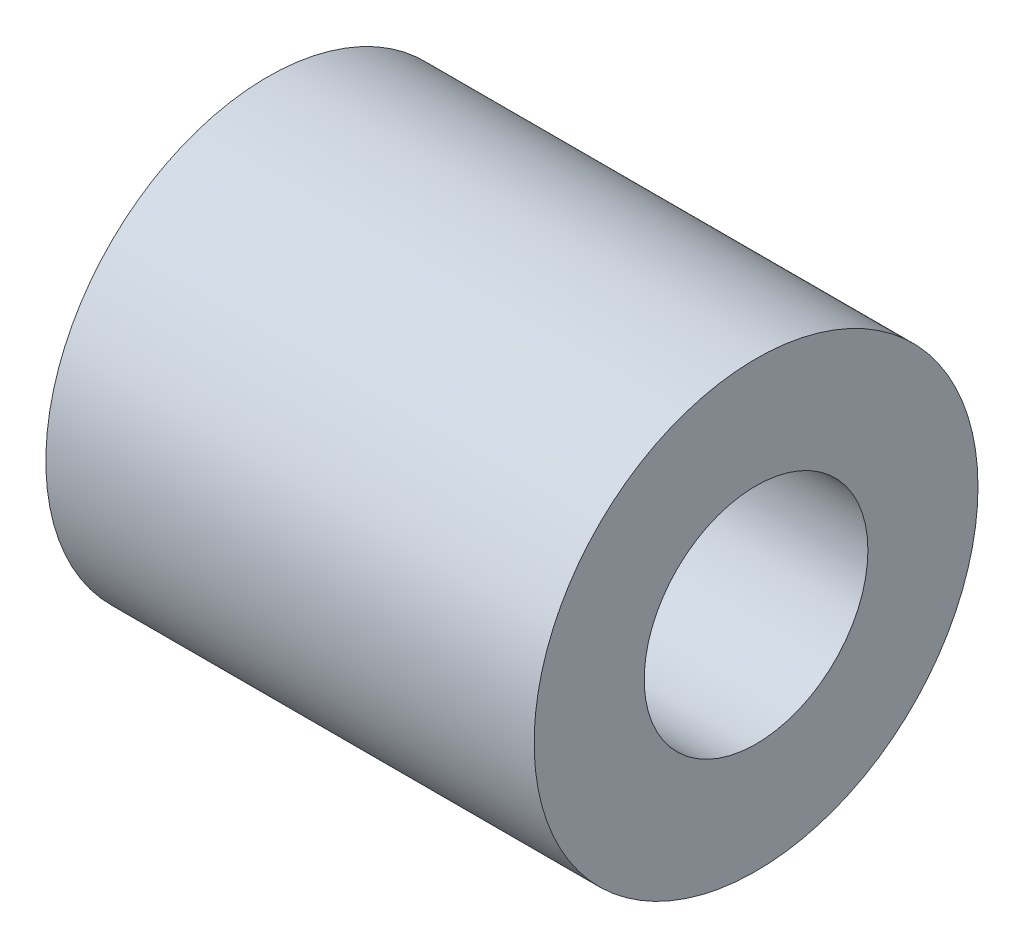
SolidWorks part; units mm, degrees
ref_plane "Front Plane" through (0, 0, 0) normal (0, 0, 1) x (1, 0, 0)
ref_plane "Top Plane" through (0, 0, 0) normal (0, 1, 0) x (1, 0, 0)
ref_plane "Right Plane" through (0, 0, 0) normal (1, 0, 0) x (0, 0, -1)
sketch "Sketch1" plane through (0, 0, 0) normal (0, 0, 1) x (1, 0, 0)
  line L0 (0, 0) -> (-18501.6239, 0) construction
  line L1 (0, 3.2004) -> (0, 6.35)
  line L2 (0, 6.35) -> (-13.97, 6.35)
  line L3 (-13.97, 6.35) -> (-13.97, 3.2004)
  line L4 (-13.97, 3.2004) -> (0, 3.2004)
  dimension "D1" = 13.97
  dimension "D2" = 12.7
  dimension "D3" = 6.4008
revolve "Revolve1" add sketch "Sketch1" angle 360 about L0
